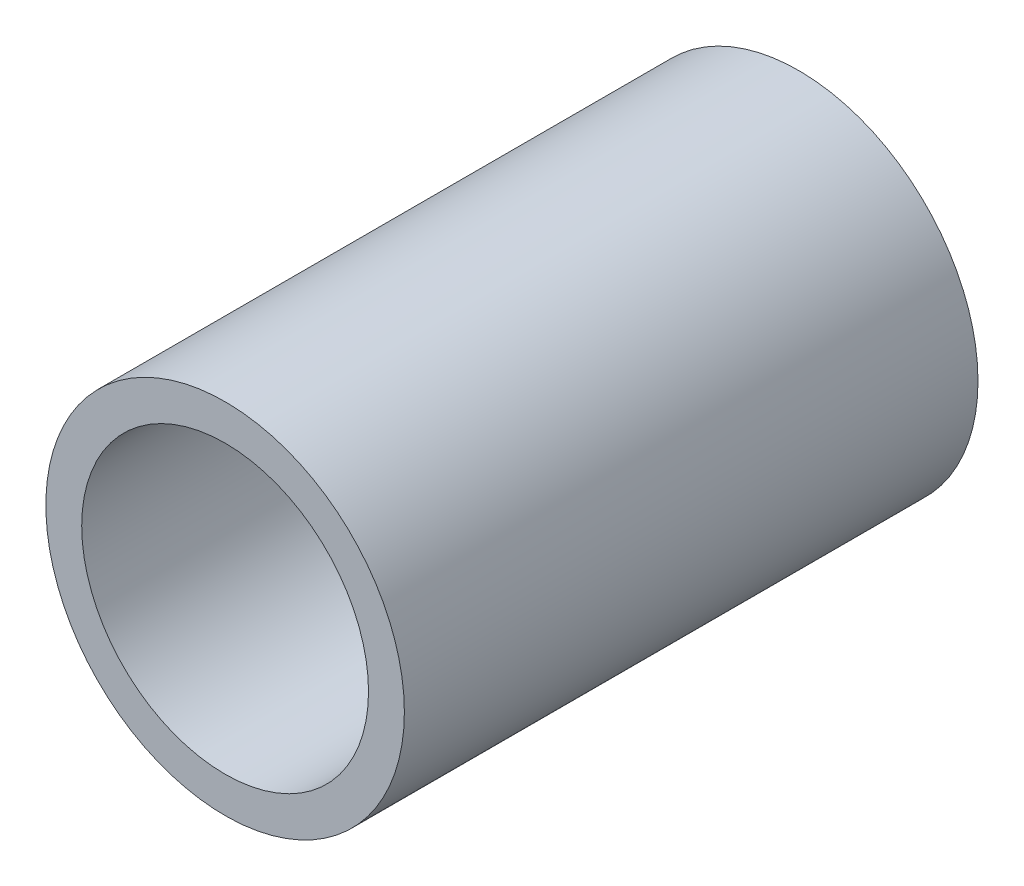
SolidWorks part; units mm, degrees
ref_plane "정면" through (0, 0, 0) normal (0, 0, 1) x (1, 0, 0)
ref_plane "윗면" through (0, 0, 0) normal (0, 1, 0) x (1, 0, 0)
ref_plane "우측면" through (0, 0, 0) normal (1, 0, 0) x (0, 0, -1)
sketch "스케치1" plane through (0, 0, 0) normal (0, 0, 1) x (1, 0, 0)
  circle A0 centre (0, 0) radius 10
  circle A1 centre (0, 0) radius 12.5
  dimension "D1" = 25
  dimension "D2" = 20
extrude "보스-돌출3" add sketch "스케치1" along normal blind 40
